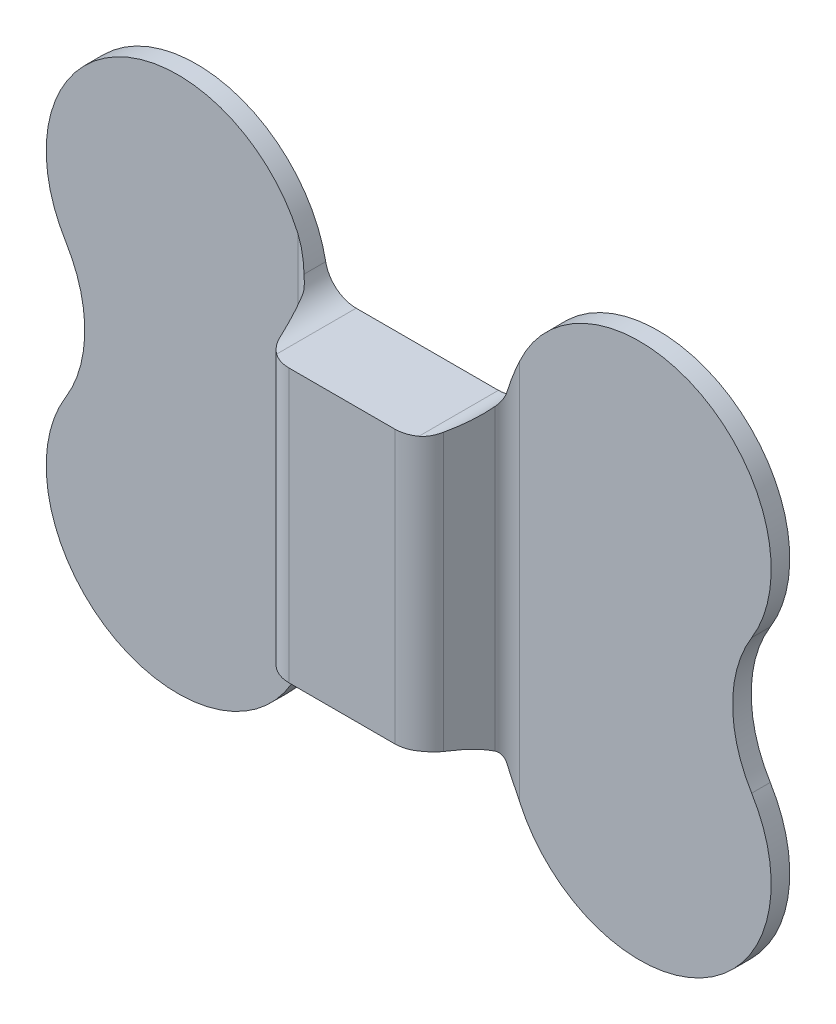
SolidWorks part; units mm, degrees
ref_plane "Front Plane" through (0, 0, 0) normal (0, 0, 1) x (1, 0, 0)
ref_plane "Top Plane" through (0, 0, 0) normal (0, 1, 0) x (1, 0, 0)
ref_plane "Right Plane" through (0, 0, 0) normal (1, 0, 0) x (0, 0, -1)
sketch "Sketch1" plane through (0, 0, 0) normal (0, 0, 1) x (1, 0, 0)
  line L0 (0, 0) -> (0, 31.402) construction
  line L1 (0, 0) -> (-57.7561, 0) construction
  line L2 (22.9612, 44) -> (-22.9612, 44)
  line L3 (22.9612, -44) -> (-22.9612, -44)
  arc A0 (110.703, 21.7381) -> (32.7781, 52.0952) centre (74.5, 44) ccw
  arc A1 (-110.703, 21.7381) -> (-32.7781, 52.0952) centre (-74.5, 44) cw
  arc A2 (110.703, -21.7381) -> (32.7781, -52.0952) centre (74.5, -44) cw
  arc A3 (-110.703, -21.7381) -> (-32.7781, -52.0952) centre (-74.5, -44) ccw
  arc A4 (110.703, 21.7381) -> (110.703, -21.7381) centre (146.0542, 0) ccw
  arc A5 (22.9612, 44) -> (32.7781, 52.0952) centre (22.9612, 54) ccw
  arc A6 (-22.9612, 44) -> (-32.7781, 52.0952) centre (-22.9612, 54) cw
  arc A7 (-110.703, 21.7381) -> (-110.703, -21.7381) centre (-146.0542, 0) cw
  arc A8 (22.9612, -44) -> (32.7781, -52.0952) centre (22.9612, -54) cw
  arc A9 (-22.9612, -44) -> (-32.7781, -52.0952) centre (-22.9612, -54) ccw
  point P23 (0, 44)
  dimension "D1" = 85
  dimension "D2" = 173
  dimension "D3" = 234
  dimension "D4" = 83
  dimension "D5" = 44
  dimension "D6" = 20
extrude "Boss-Extrude1" add sketch "Sketch1" along normal blind 27.56
sketch "Sketch2" plane through (0, 0, 0) normal (0, 1, 0) x (1, 0, 0)
  line L0 (117, -6) -> (35.7676, -6)
  line L1 (117, -27.56) -> (117, 0) construction
  line L2 (31.1085, -9.1854) -> (26.4332, -21.1893)
  line L3 (22.9612, -27.56) -> (32.7781, -27.56) construction
  line L9 (0, -1013.78) -> (0, 48986.22) construction
  line L10 (17.115, -27.56) -> (117, -27.56)
  line L11 (117, -27.56) -> (117, -6)
  line L12 (117, 0) -> (32.7781, 0) construction
  line L13 (-117, -27.56) -> (-117, -6)
  line L14 (-17.115, -27.56) -> (-117, -27.56)
  line L15 (-31.1085, -9.1854) -> (-26.4332, -21.1893)
  line L16 (-117, -6) -> (-35.7676, -6)
  arc A0 (26.4332, -21.1893) -> (17.115, -27.56) centre (17.115, -17.56) cw
  arc A1 (35.7676, -6) -> (31.1085, -9.1854) centre (35.7676, -11) ccw
  arc A2 (-35.7676, -6) -> (-31.1085, -9.1854) centre (-35.7676, -11) cw
  arc A3 (-26.4332, -21.1893) -> (-17.115, -27.56) centre (-17.115, -17.56) ccw
  point P20 (23.9519, -27.56)
  point P29 (-23.9519, -27.56)
  dimension "D3" = 10
  dimension "D4" = 5
  dimension "D1" = 17.115
  dimension "D2" = 111.28
  dimension "D5" = 6
extrude "Cut-Extrude1" cut sketch "Sketch2" against normal through all both and the other way through all
